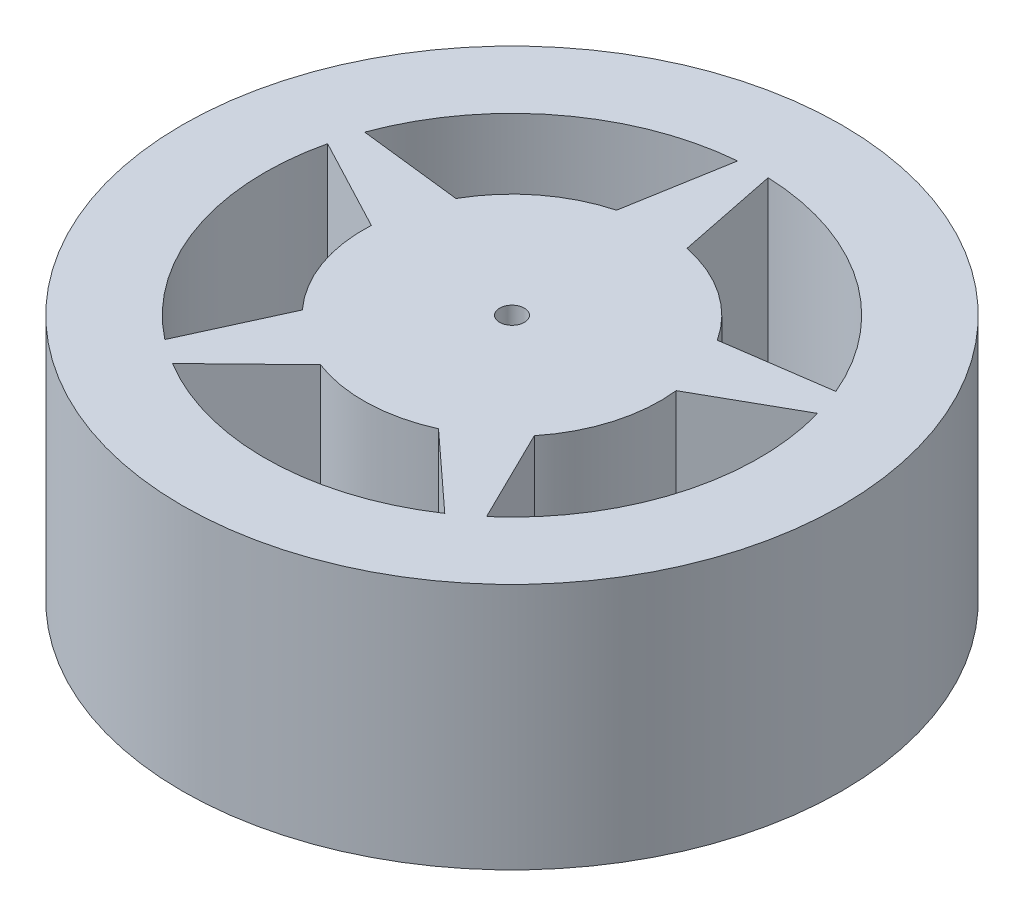
SolidWorks part; units mm, degrees
ref_plane "Front Plane" through (0, 0, 0) normal (0, 0, 1) x (1, 0, 0)
ref_plane "Top Plane" through (0, 0, 0) normal (0, 1, 0) x (1, 0, 0)
ref_plane "Right Plane" through (0, 0, 0) normal (1, 0, 0) x (0, 0, -1)
sketch "Sketch1" plane through (0, 0, 0) normal (0, 1, 0) x (1, 0, 0)
  circle A0 centre (0, 0) radius 40
extrude "Boss-Extrude1" add sketch "Sketch1" along normal blind 30
sketch "Sketch2" plane through (0, 30, 0) normal (0, 1, 0) x (1, 0, 0)
  line L0 (-2.5242, 29.8936) -> (-4.6908, 17.378)
  line L1 (1.0907, 29.9802) -> (3.5892, 17.6385)
  line L2 (27.6505, 11.6383) -> (15.0779, 9.8314)
  line L3 (28.8499, 8.2271) -> (17.8844, 2.0371)
  line L4 (19.6132, -22.7008) -> (14.0095, -11.3019)
  line L5 (16.7395, -24.8956) -> (7.4639, -16.3796)
  line L6 (-15.5289, -25.6681) -> (-6.4196, -16.8163)
  line L7 (-18.5043, -23.6134) -> (-13.2714, -12.1602)
  line L8 (-29.2105, 6.837) -> (-17.977, 0.9089)
  line L9 (-28.1758, 10.3017) -> (-15.6661, 8.8641)
  arc A0 (-17.977, 0.9089) -> (-13.2714, -12.1602) centre (0, 0) ccw
  arc A1 (-29.2105, 6.837) -> (-18.5043, -23.6134) centre (0, 0) ccw
  circle A2 centre (0, 0) radius 32
  circle A3 centre (0, 0) radius 1.5
  arc A4 (-15.5289, -25.6681) -> (16.7395, -24.8956) centre (0, 0) ccw
  arc A5 (19.6132, -22.7008) -> (28.8499, 8.2271) centre (0, 0) ccw
  arc A6 (27.6505, 11.6383) -> (1.0907, 29.9802) centre (0, 0) ccw
  arc A7 (-2.5242, 29.8936) -> (-28.1758, 10.3017) centre (0, 0) ccw
  arc A8 (-6.4196, -16.8163) -> (7.4639, -16.3796) centre (0, 0) ccw
  arc A9 (14.0095, -11.3019) -> (17.8844, 2.0371) centre (0, 0) ccw
  arc A10 (15.0779, 9.8314) -> (3.5892, 17.6385) centre (0, 0) ccw
  arc A11 (-4.6908, 17.378) -> (-15.6661, 8.8641) centre (0, 0) ccw
  point P26 (0, 0)
  dimension "D1" = 5
extrude "Cut-Extrude2" cut sketch "Sketch2" against normal blind 40 contours L9 A11 L0 A7 | L2 A10 L1 A6 | L4 A9 L3 A5 | L6 A8 L5 A4 | L8 A0 L7 A1
sketch "Sketch4" plane through (0, 30, 0) normal (0, 1, 0) x (1, 0, 0)
  circle A0 centre (0, 0) radius 1.5
extrude "Cut-Extrude3" cut sketch "Sketch4" against normal blind 40
